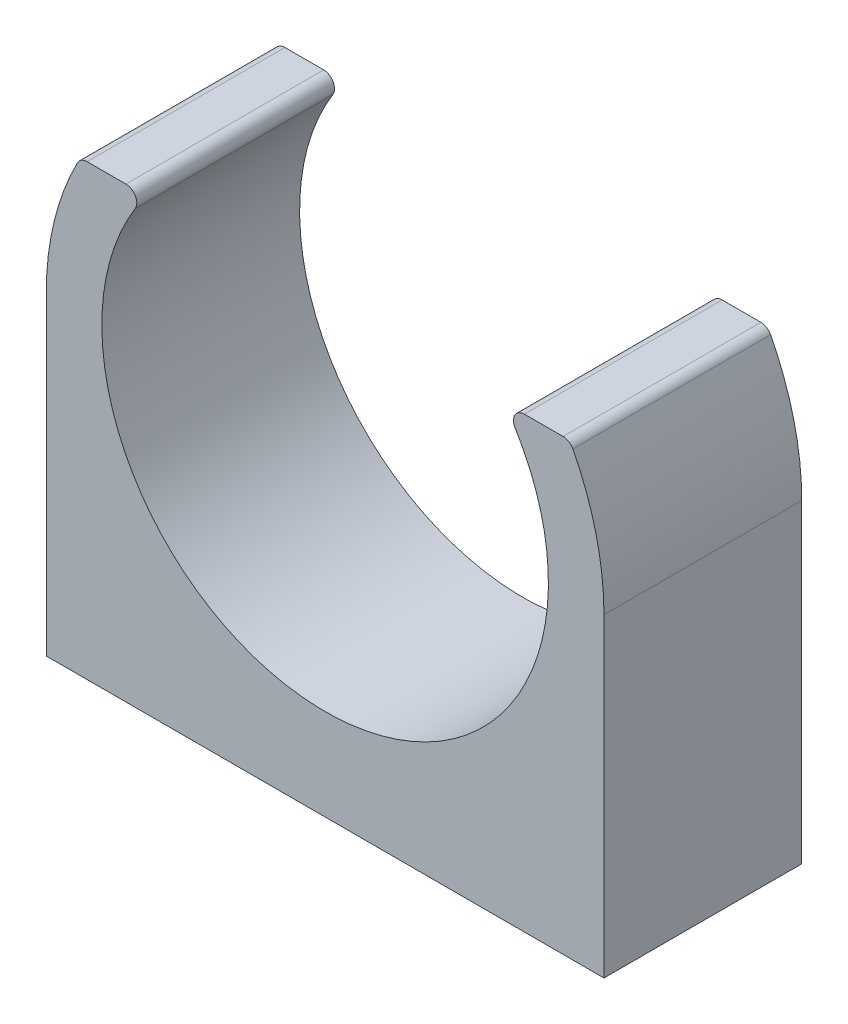
SolidWorks part; units mm, degrees
ref_plane "Front Plane" through (0, 0, 0) normal (0, 0, 1) x (1, 0, 0)
ref_plane "Top Plane" through (0, 0, 0) normal (0, 1, 0) x (1, 0, 0)
ref_plane "Right Plane" through (0, 0, 0) normal (1, 0, 0) x (0, 0, -1)
sketch "Sketch1" plane through (0, 0, 0) normal (0, 0, 1) x (1, 0, 0)
  line L0 (-21.15, 0) -> (21.15, 0)
  line L1 (-21.15, 0) -> (-21.15, 20.1112)
  line L3 (21.15, 0) -> (21.15, 20.1112)
  line L6 (-18.5498, 30.2712) -> (-13.5502, 30.2712)
  line L7 (13.5502, 30.2712) -> (18.5498, 30.2712)
  line L11 (-21.15, 20.1112) -> (21.15, 20.1112) construction
  line L12 (-21.15, 0) -> (21.15, 0)
  line L13 (-21.15, 0) -> (-21.15, -3.75)
  line L14 (21.15, 0) -> (21.15, -3.75)
  line L15 (-21.15, -3.75) -> (21.15, -3.75)
  arc A0 (-13.5502, 30.2712) -> (13.5502, 30.2712) centre (0, 20.1112) ccw
  arc A1 (-18.5498, 30.2712) -> (-21.15, 20.1112) centre (0, 20.1112) ccw
  arc A2 (-16.9216, 32.7991) -> (16.9216, 32.7991) centre (0, 20.1112) ccw construction
  arc A3 (21.15, 20.1112) -> (18.5498, 30.2712) centre (0, 20.1112) ccw
  point P2 (0, 20.1112)
  dimension "D6" = 33.8724
  dimension "D1" = 3.175
  dimension "D2" = 42.3
  dimension "D3" = 10.16
  dimension "D4" = 3.75
extrude "Boss-Extrude1" add sketch "Sketch1" along normal blind 15 contours L3 A3 L7 A0 L6 A1 L1 L0 | L13 L15 L14 L0
fillet "Fillet1" radius 0.8255 4 edges at (13.5502, 30.2712, 7.5) (-13.5502, 30.2712, 7.5) (18.5498, 30.2712, 7.5) (-18.5498, 30.2712, 7.5)
